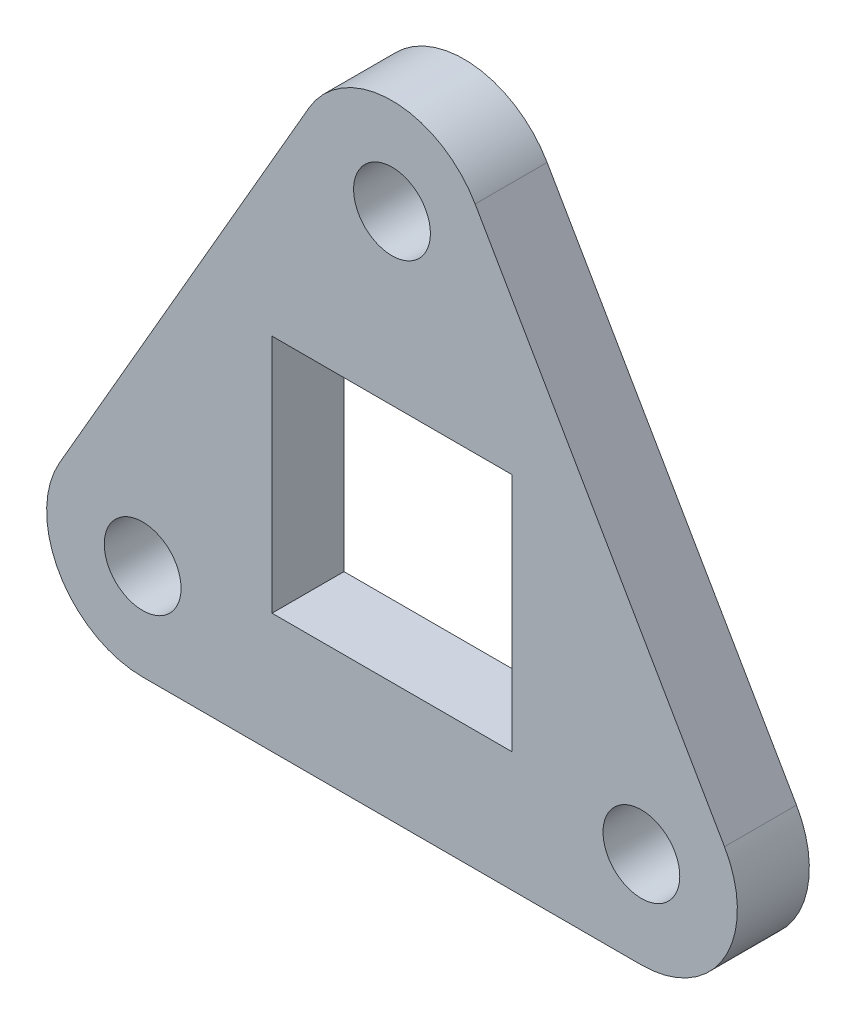
SolidWorks part; units mm, degrees
material "ﾎﾟﾘｶｰﾎﾞﾈｰﾄ(PC)高粘度"
ref_plane "正面" through (0, 0, 0) normal (0, 0, 1) x (1, 0, 0)
ref_plane "平面" through (0, 0, 0) normal (0, 1, 0) x (1, 0, 0)
ref_plane "右側面" through (0, 0, 0) normal (1, 0, 0) x (0, 0, -1)
sketch "ｽｹｯﾁ1" plane through (0, 0, 0) normal (0, 0, 1) x (1, 0, 0)
  line L0 (0, 0) -> (0, 12) construction
  line L1 (5, -5) -> (-5, -5)
  line L2 (5, -5) -> (5, 5)
  line L3 (5, 5) -> (-5, 5)
  line L4 (-5, -5) -> (-5, 5)
  line L5 (5, -5) -> (-5, 5) construction
  line L6 (5, 5) -> (-5, -5) construction
  line L7 (0, 0) -> (10.3923, -6) construction
  line L8 (0, 0) -> (-10.3923, -6) construction
  line L9 (-13.8564, -4) -> (-3.4641, 14)
  line L10 (-10.3923, -10) -> (10.3923, -10)
  line L11 (3.4641, 14) -> (13.8564, -4)
  circle A0 centre (0, 12) radius 1.6
  circle A1 centre (10.3923, -6) radius 1.6
  circle A2 centre (-10.3923, -6) radius 1.6
  arc A3 (-3.4641, 14) -> (3.4641, 14) centre (0, 12) cw
  arc A4 (-13.8564, -4) -> (-10.3923, -10) centre (-10.3923, -6) ccw
  arc A5 (10.3923, -10) -> (13.8564, -4) centre (10.3923, -6) ccw
  point P0 (0, 0)
  point P15 (0, 0)
  point P17 (-15.5868, -6.9971)
  point P18 (12.843, -2.8387)
  point P26 (-1.9975, 16.5403)
  point P27 (3.2988, 14.2863)
  point P28 (-13.082, -10)
  dimension "D1" = 3.2
  dimension "D5" = 4
  dimension "D2" = 10
  dimension "D3" = 12
  dimension "D4" = 3
extrude "ﾎﾞｽ - 押し出し1" add sketch "ｽｹｯﾁ1" along normal blind 3
